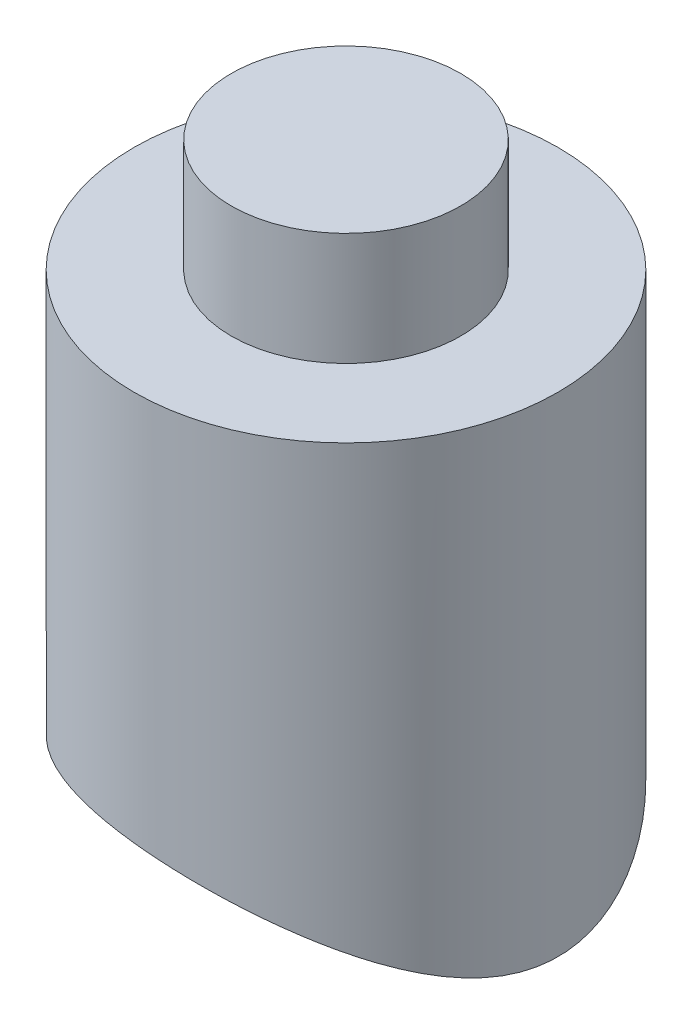
SolidWorks part; units mm, degrees
ref_plane "Front Plane" through (0, 0, 0) normal (0, 0, 1) x (1, 0, 0)
ref_plane "Top Plane" through (0, 0, 0) normal (0, 1, 0) x (1, 0, 0)
ref_plane "Right Plane" through (0, 0, 0) normal (1, 0, 0) x (0, 0, -1)
sketch "Sketch1" plane through (0, 0, 0) normal (0, 1, 0) x (1, 0, 0)
  circle A0 centre (0, 0) radius 1.375
  dimension "D1" = 2.75
extrude "Boss-Extrude1" add sketch "Sketch1" along normal blind 1.35
sketch "Sketch2" plane through (0, 0, 0) normal (0, -1, 0) x (1, 0, 0)
  circle A0 centre (0, 0) radius 2.54
  dimension "D1" = 5.08
extrude "Boss-Extrude2" add sketch "Sketch2" along normal blind 9.144
sketch "Sketch3" plane through (0, 0, 0) normal (0, 0, 1) x (1, 0, 0)
  line L0 (-2.54, -9.144) -> (2.54, -9.144) construction
  line L1 (0, 0) -> (0, -14.8306) construction
  circle A1 centre (-0.5334, -9.144) radius 4.5
  dimension "D1" = 0.5334
extrude "Cut-Extrude1" cut sketch "Sketch3" along normal mid plane 7.62
